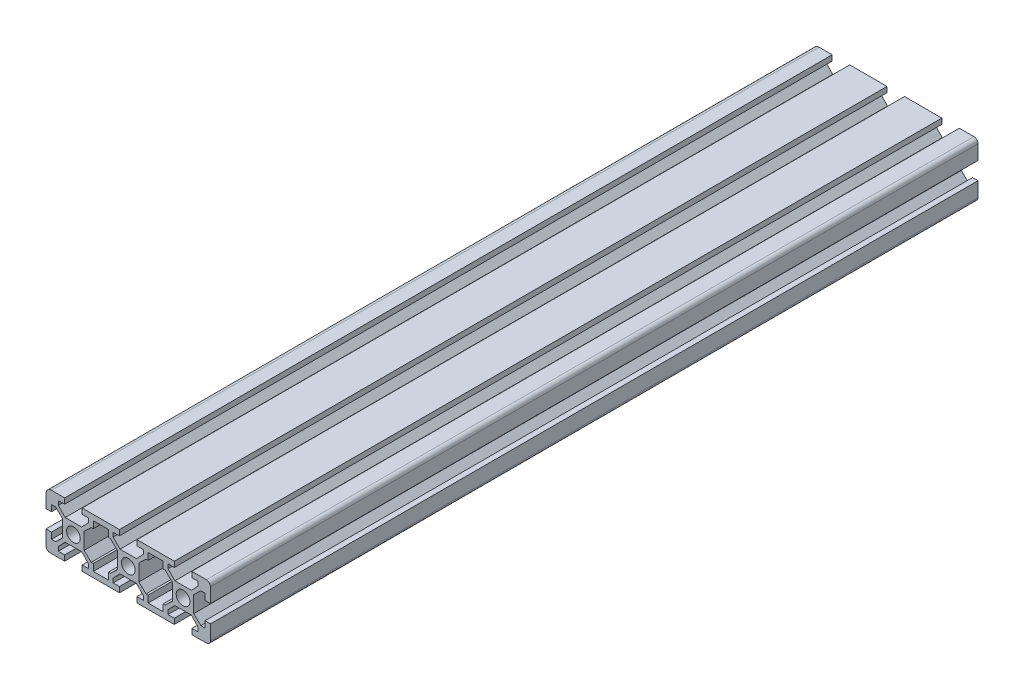
SolidWorks part; units mm, degrees
ref_plane "前视基准面" through (0, 0, 0) normal (0, 0, 1) x (1, 0, 0)
ref_plane "上视基准面" through (0, 0, 0) normal (0, 1, 0) x (1, 0, 0)
ref_plane "右视基准面" through (0, 0, 0) normal (1, 0, 0) x (0, 0, -1)
sketch "草图1" plane through (0, 0, 0) normal (0, 0, 1) x (1, 0, 0)
  line L1 (-28, 10) -> (28.5, 10)
  line L2 (-30, 8) -> (-30, -8.5)
  line L3 (-28.5, -10) -> (28.5, -10)
  line L4 (30, 8.5) -> (30, -8.5)
  line L5 (-30, 10) -> (30, -10) construction
  line L6 (-30, -10) -> (30, 10) construction
  line L7 (-30, -3.2) -> (-28, -3.2)
  line L13 (-16.8, 8) -> (-16.8, 10)
  line L14 (-14.5, 8) -> (-16.8, 8)
  line L15 (-14.5, 6.5) -> (-14.5, 8)
  line L16 (-17, 3.9) -> (-14.5, 6.5)
  line L17 (-23, 3.9) -> (-17, 3.9)
  line L18 (-25.5, 6.5) -> (-23, 3.9)
  line L25 (-28, -3.2) -> (-28, -5.5)
  line L26 (-28, -5.5) -> (-26.5, -5.5)
  line L27 (-26.5, -5.5) -> (-23.9, -3)
  line L28 (-23.9, -3) -> (-23.9, 3)
  line L29 (-23.9, 3) -> (-26.5, 5.5)
  line L30 (-26.5, 5.5) -> (-28, 5.5)
  line L31 (-28, 5.5) -> (-28, 3.2)
  line L32 (-28, 3.2) -> (-30, 3.2)
  line L33 (-25.5, 8) -> (-25.5, 6.5)
  line L34 (-23.2, 8) -> (-25.5, 8)
  line L35 (-23.2, 10) -> (-23.2, 8)
  line L36 (-12, -3.2) -> (-8, -3.2)
  line L37 (-12, -5.5) -> (-12, -3.2)
  line L38 (-13.5, -5.5) -> (-12, -5.5)
  line L39 (-16.1, -3) -> (-13.5, -5.5)
  line L40 (-16.1, 3) -> (-16.1, -3)
  line L41 (-13.5, 5.5) -> (-16.1, 3)
  line L42 (-12, 5.5) -> (-13.5, 5.5)
  line L43 (-12, 3.2) -> (-12, 5.5)
  line L44 (-8, 3.2) -> (-12, 3.2)
  line L45 (-23.2, -8) -> (-23.2, -10)
  line L46 (-25.5, -8) -> (-23.2, -8)
  line L47 (-25.5, -6.5) -> (-25.5, -8)
  line L48 (-23, -3.9) -> (-25.5, -6.5)
  line L49 (-17, -3.9) -> (-23, -3.9)
  line L50 (-14.5, -6.5) -> (-17, -3.9)
  line L51 (-14.5, -8) -> (-14.5, -6.5)
  line L52 (-16.8, -8) -> (-14.5, -8)
  line L53 (-16.8, -10) -> (-16.8, -8)
  line L54 (-10, 3.2) -> (-10, -3.2) construction
  line L55 (-10, -3.2) -> (-10, 3.2) construction
  line L56 (3, 3.9) -> (-3, 3.9)
  line L57 (5.5, 6.5) -> (3, 3.9)
  line L58 (5.5, 8) -> (5.5, 6.5)
  line L59 (3.2, 8) -> (5.5, 8)
  line L60 (3.2, 10) -> (3.2, 8)
  line L61 (-3.2, 8) -> (-3.2, 10)
  line L62 (-5.5, 8) -> (-3.2, 8)
  line L63 (-5.5, 6.5) -> (-5.5, 8)
  line L64 (-3, 3.9) -> (-5.5, 6.5)
  line L65 (-6.5, 5.5) -> (-3.9, 3)
  line L66 (-8, 5.5) -> (-6.5, 5.5)
  line L67 (-8, 3.2) -> (-8, 5.5)
  line L68 (-8, -5.5) -> (-8, -3.2)
  line L69 (-6.5, -5.5) -> (-8, -5.5)
  line L70 (-3.9, -3) -> (-6.5, -5.5)
  line L71 (-3.9, 3) -> (-3.9, -3)
  line L72 (-3, -3.9) -> (3, -3.9)
  line L73 (-5.5, -6.5) -> (-3, -3.9)
  line L74 (-5.5, -8) -> (-5.5, -6.5)
  line L75 (-3.2, -8) -> (-5.5, -8)
  line L76 (-3.2, -10) -> (-3.2, -8)
  line L77 (3.2, -8) -> (3.2, -10)
  line L78 (5.5, -8) -> (3.2, -8)
  line L79 (5.5, -6.5) -> (5.5, -8)
  line L80 (3, -3.9) -> (5.5, -6.5)
  line L81 (3.9, -3) -> (3.9, 3)
  line L82 (6.5, -5.5) -> (3.9, -3)
  line L83 (8, -5.5) -> (6.5, -5.5)
  line L84 (8, -3.2) -> (8, -5.5)
  line L85 (12, -3.2) -> (8, -3.2)
  line L86 (8, 3.2) -> (12, 3.2)
  line L87 (8, 5.5) -> (8, 3.2)
  line L88 (6.5, 5.5) -> (8, 5.5)
  line L89 (3.9, 3) -> (6.5, 5.5)
  line L90 (10, 3.2) -> (10, -3.133) construction
  line L91 (23.2, 8) -> (23.2, 10)
  line L92 (25.5, 8) -> (23.2, 8)
  line L93 (25.5, 6.5) -> (25.5, 8)
  line L94 (23, 3.9) -> (25.5, 6.5)
  line L95 (17, 3.9) -> (23, 3.9)
  line L96 (16.8, 10) -> (16.8, 8)
  line L97 (16.8, 8) -> (14.5, 8)
  line L98 (14.5, 8) -> (14.5, 6.5)
  line L99 (14.5, 6.5) -> (17, 3.9)
  line L100 (16.1, 3) -> (13.5, 5.5)
  line L101 (13.5, 5.5) -> (12, 5.5)
  line L102 (12, 5.5) -> (12, 3.2)
  line L103 (12, -3.2) -> (12, -5.5)
  line L104 (12, -5.5) -> (13.5, -5.5)
  line L105 (16.1, -3) -> (16.1, 3)
  line L106 (13.5, -5.5) -> (16.1, -3)
  line L107 (17, -3.9) -> (14.5, -6.5)
  line L108 (14.5, -6.5) -> (14.5, -8)
  line L109 (14.5, -8) -> (16.8, -8)
  line L110 (16.8, -8) -> (16.8, -10)
  line L111 (23.2, -10) -> (23.2, -8)
  line L112 (23.2, -8) -> (25.5, -8)
  line L113 (25.5, -8) -> (25.5, -6.5)
  line L114 (25.5, -6.5) -> (23, -3.9)
  line L115 (23, -3.9) -> (17, -3.9)
  line L116 (28, 3.2) -> (30, 3.2)
  line L117 (30, -3.2) -> (28, -3.2)
  line L118 (28, -5.5) -> (28, -3.2)
  line L119 (26.5, -5.5) -> (28, -5.5)
  line L120 (23.9, -3) -> (26.5, -5.5)
  line L121 (23.9, 3) -> (23.9, -3)
  line L122 (26.5, 5.5) -> (23.9, 3)
  line L123 (28, 5.5) -> (26.5, 5.5)
  line L124 (28, 3.2) -> (28, 5.5)
  line L125 (-12.75, 5.5) -> (-12.75, 8)
  line L126 (-7.25, 5.5) -> (-7.25, 8)
  line L127 (-7.25, 8) -> (-12.75, 8)
  line L128 (-12.75, -5.5) -> (-12.75, -8)
  line L129 (-7.25, -5.5) -> (-7.25, -8)
  line L130 (-7.25, -8) -> (-12.75, -8)
  line L131 (7.25, 5.5) -> (7.25, 8)
  line L132 (12.75, 5.5) -> (12.75, 8)
  line L133 (12.75, 8) -> (7.25, 8)
  line L134 (7.25, -5.5) -> (7.25, -8)
  line L135 (12.75, -5.5) -> (12.75, -8)
  line L136 (12.75, -8) -> (7.25, -8)
  circle A0 centre (0, 0) radius 2.5
  circle A1 centre (-20, 0) radius 2.5
  circle A2 centre (20, 0) radius 2.5
  arc A3 (-30, 8) -> (-28, 10) centre (-28, 8) cw
  arc A4 (-30, -8.5) -> (-28.5, -10) centre (-28.5, -8.5) ccw
  arc A5 (28.5, -10) -> (30, -8.5) centre (28.5, -8.5) ccw
  arc A6 (30, 8.5) -> (28.5, 10) centre (28.5, 8.5) ccw
  point P0 (0, 0)
  point P63 (-20, 0)
  point P115 (10, -3.2)
  dimension "D1" = 20
  dimension "D7" = 5
  dimension "D8" = 5
  dimension "D9" = 5
  dimension "D5" = 2
  dimension "D6" = 1.5
  dimension "D12" = 1.5
  dimension "D2" = 20
  dimension "D3" = 60
  dimension "D4" = 20
  dimension "D10" = 6.1
  dimension "D11" = 2.3
  dimension "D14" = 6.4
  dimension "D15" = 13.2
  dimension "D16" = 11
  dimension "D17" = 10
  dimension "D18" = 6
  dimension "D19" = 1.5
  dimension "D20" = 2
  dimension "D21" = 2
  dimension "D22" = 1.5
  dimension "D23" = 7
extrude "凸台-拉伸2" add sketch "草图1" along normal blind 280 contours L4 A6 L1 L91 L92 L93 L94 L95 L99 L98 L97 L96 L60 L59 L58 L57 L56 L64 L63 L62 L61 L13 L14 L15 L16 L17 L18 L33 L34 L35 A3 L2 L32 L31 L30 L29 L28 L27 L26 L25 L7 A4 L3 L45 L46 L47 L48
